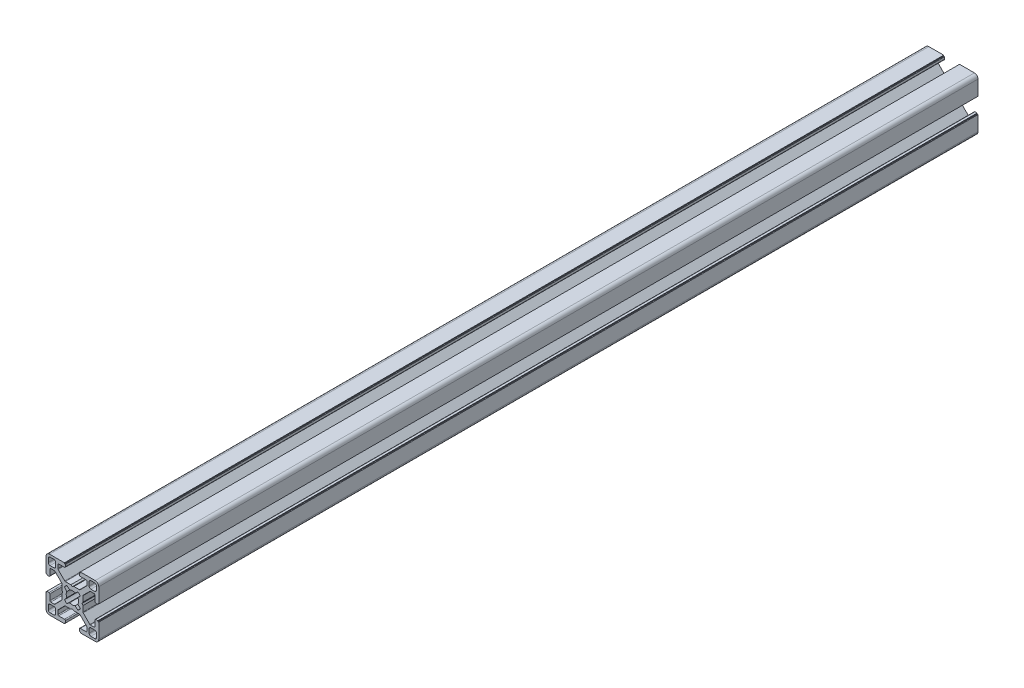
SolidWorks part; units mm, degrees
ref_plane "Front Plane" through (0, 0, 0) normal (0, 0, 1) x (1, 0, 0)
ref_plane "Top Plane" through (0, 0, 0) normal (0, 1, 0) x (1, 0, 0)
ref_plane "Right Plane" through (0, 0, 0) normal (1, 0, 0) x (0, 0, -1)
sketch "Sketch1" plane through (0, 0, 0) normal (0, 0, 1) x (1, 0, 0)
  line L0 (-15, 0) -> (15, 0) construction
  line L1 (0, -15) -> (0, 15) construction
  line L2 (-4.5, 15) -> (4.5, 15) construction
  line L3 (-4, -15) -> (4, -15) construction
  line L4 (-4.5, 15) -> (-4.5, 14.5)
  line L5 (-4.5, 14.5) -> (-4, 14.5)
  line L6 (-4, 14.5) -> (-4, 13.29)
  line L7 (-4.5, 12.79) -> (-7.7675, 12.79)
  line L8 (-8.2675, 12.29) -> (-8.2675, 10.2707)
  line L9 (-8.1211, 9.9171) -> (-4.3504, 6.1464)
  line L10 (-3.9968, 6) -> (0, 6)
  line L11 (0, 0) -> (-15, 15) construction
  line L12 (-4.5, 15) -> (-12.968, 15)
  line L14 (-12.705, 9.5135) -> (-10.5135, 9.5135)
  line L15 (-13.705, 10.5135) -> (-13.705, 12.705)
  line L16 (-12.705, 13.705) -> (-10.5135, 13.705)
  line L17 (-9.5135, 10.5135) -> (-9.5135, 12.705)
  line L18 (-13.705, 9.5135) -> (-9.5135, 13.705) construction
  line L19 (-13.705, 13.705) -> (-9.5135, 9.5135) construction
  line L20 (-3.1568, 4.5038) -> (-1.5303, 3.1477) construction
  line L21 (-4.5038, 3.1568) -> (-3.1477, 1.5303) construction
  line L22 (-6, 3.9968) -> (-6, 0)
  line L23 (-9.9171, 8.1211) -> (-6.1464, 4.3504)
  line L24 (-15, 4.5) -> (-15, 12.968)
  line L25 (-12.29, 8.2675) -> (-10.2707, 8.2675)
  line L26 (-12.79, 4.5) -> (-12.79, 7.7675)
  line L27 (-14.5, 4) -> (-13.29, 4)
  line L28 (-14.5, 4.5) -> (-14.5, 4)
  line L29 (-15, 4.5) -> (-14.5, 4.5)
  circle A0 centre (0, 0) radius 3.5
  arc A1 (-12.968, 15) -> (-15, 12.968) centre (-12.968, 12.968) ccw
  circle A2 centre (0, 0) radius 5.5 construction
  arc A3 (-10.5135, 9.5135) -> (-9.5135, 10.5135) centre (-10.5135, 10.5135) ccw
  arc A4 (-13.705, 12.705) -> (-12.705, 13.705) centre (-12.705, 12.705) cw
  arc A5 (-10.5135, 13.705) -> (-9.5135, 12.705) centre (-10.5135, 12.705) cw
  arc A6 (-12.705, 9.5135) -> (-13.705, 10.5135) centre (-12.705, 10.5135) cw
  arc A7 (-12.79, 4.5) -> (-13.29, 4) centre (-13.29, 4.5) cw
  arc A8 (-12.29, 8.2675) -> (-12.79, 7.7675) centre (-12.29, 7.7675) ccw
  arc A9 (-9.9171, 8.1211) -> (-10.2707, 8.2675) centre (-10.2707, 7.7675) ccw
  arc A10 (-6, 3.9968) -> (-6.1464, 4.3504) centre (-6.5, 3.9968) ccw
  arc A11 (-4.3504, 6.1464) -> (-3.9968, 6) centre (-3.9968, 6.5) ccw
  arc A12 (-4, 13.29) -> (-4.5, 12.79) centre (-4.5, 13.29) cw
  arc A13 (-7.7675, 12.79) -> (-8.2675, 12.29) centre (-7.7675, 12.29) ccw
  arc A14 (-8.2675, 10.2707) -> (-8.1211, 9.9171) centre (-7.7675, 10.2707) ccw
  point P4 (0, 0)
  point P8 (0, 0)
  point P13 (0, 15)
  point P15 (0, -15)
  point P16 (0, 6)
  point P23 (-11.6092, 11.6093)
  point P26 (0, 6)
  point P62 (-12.79, 4)
  point P65 (-12.79, 8.2675)
  point P68 (-10.0636, 8.2675)
  point P71 (-6, 4.2039)
  point P74 (-4.2039, 6)
  point P77 (-4, 12.79)
  point P80 (-8.2675, 12.79)
  point P83 (-8.2675, 10.0636)
  dimension "Center Hole Diameter" = 7
  dimension "D11" = 2.032
  dimension "D9" = 11
  dimension "D13" = 1
  dimension "D14" = 0.5
  dimension "Rail Height" = 30
  dimension "Rail Width" = 30
  dimension "T-Slot Width" = 8
  dimension "T-Slot Depth" = 9
  dimension "D1" = 9
  dimension "D2" = 45
  dimension "D3" = 8
  dimension "D4" = 2.21
  dimension "D5" = 16.535
  dimension "D7" = 2.54
  dimension "D6" = 1.295
  dimension "D8" = 1.246
  dimension "D10" = 10.36
  dimension "D12" = 1.905
sketch "Sketch2" plane through (0, 0, 0) normal (1, 0, 0) x (0, 0, -1)
  line L0 (-76.2, 0) -> (76.2, 0) construction
  line L2 (0, -15) -> (0, 15) construction
  line L3 (0, -15) -> (0, 15) construction
  line L4 (-76.2, -15) -> (-76.2, 15) construction
  line L5 (76.2, -15) -> (76.2, 15) construction
  point P0 (-38.7, 0)
  point P3 (0, 0)
  point P4 (38.7, 0)
  point P12 (-76.2, 0)
  point P14 (76.2, 0)
  dimension "Length" = 152.4
  dimension "D1" = 37.5
sketch "Sketch3" plane through (0, 0, 0) normal (0, 0, 1) x (1, 0, 0)
  line L0 (-4.5038, 3.1568) -> (-3.1477, 1.5303)
  line L1 (0, 3.5) -> (0, 5.5)
  line L2 (-5.5, 0) -> (-3.5, 0)
  line L7 (-6, 3.9968) -> (-6, 0) construction
  line L31 (-9.9171, 8.1211) -> (-6.1464, 4.3504) construction
  line L117 (-12.29, 8.2675) -> (-10.2707, 8.2675) construction
  line L118 (-12.79, 4.5) -> (-12.79, 7.7675) construction
  line L157 (-12.705, 9.5135) -> (-10.5135, 9.5135)
  line L158 (-9.5135, 10.5135) -> (-9.5135, 12.705)
  line L163 (-10.5135, 13.705) -> (-12.705, 13.705)
  line L164 (-13.705, 12.705) -> (-13.705, 10.5135)
  line L165 (-12.705, 9.5135) -> (-10.5135, 9.5135)
  line L166 (-9.5135, 10.5135) -> (-9.5135, 12.705)
  line L167 (-10.5135, 13.705) -> (-12.705, 13.705)
  line L168 (-13.705, 12.705) -> (-13.705, 10.5135)
  line L169 (-14.5, 4) -> (-13.29, 4) construction
  line L170 (-14.5, 4.5) -> (-14.5, 4) construction
  line L171 (-15, 4.5) -> (-14.5, 4.5) construction
  line L172 (-15, 4.5) -> (-15, 12.968) construction
  line L173 (-4.5, 15) -> (-12.968, 15) construction
  line L174 (-4.5, 15) -> (-4.5, 14.5) construction
  line L175 (-4.5, 14.5) -> (-4, 14.5) construction
  line L176 (-4, 14.5) -> (-4, 13.29) construction
  line L177 (-4.5, 12.79) -> (-7.7675, 12.79) construction
  line L178 (-8.2675, 12.29) -> (-8.2675, 10.2707) construction
  line L179 (-8.1211, 9.9171) -> (-4.3504, 6.1464) construction
  line L180 (-3.9968, 6) -> (0, 6) construction
  line L181 (-6, 3.9968) -> (-6, 0.866)
  line L182 (-9.9171, 8.1211) -> (-6.1464, 4.3504)
  line L183 (-12.29, 8.2675) -> (-10.2707, 8.2675)
  line L184 (-12.79, 4.5) -> (-12.79, 7.7675)
  line L185 (-14.5, 4) -> (-13.29, 4)
  line L186 (-14.5, 4.5) -> (-14.5, 4)
  line L187 (-15, 4.5) -> (-14.5, 4.5)
  line L188 (-15, 4.5) -> (-15, 12.968)
  line L189 (-4.5, 15) -> (-12.968, 15)
  line L190 (-4.5, 15) -> (-4.5, 14.5)
  line L191 (-4.5, 14.5) -> (-4, 14.5)
  line L192 (-4, 14.5) -> (-4, 13.29)
  line L193 (-4.5, 12.79) -> (-7.7675, 12.79)
  line L194 (-8.2675, 12.29) -> (-8.2675, 10.2707)
  line L195 (-8.1211, 9.9171) -> (-4.3504, 6.1464)
  line L196 (-3.9968, 6) -> (-0.866, 6)
  line L197 (-0.866, 6) -> (0, 5.5)
  line L198 (0, -15) -> (0, 15) construction
  line L199 (0, 0) -> (-15, 15) construction
  line L200 (0, 0) -> (-15, 15) construction
  line L201 (-3.1568, 4.5038) -> (-1.5303, 3.1477) construction
  line L202 (-3.1568, 4.5038) -> (-1.5303, 3.1477)
  line L203 (-6, 0.866) -> (-5.5, 0)
  line L204 (-15, 0) -> (15, 0) construction
  line L205 (-15, 0) -> (15, 0) construction
  line L206 (0, -15) -> (0, 15) construction
  arc A0 (-3.5, 0) -> (-3.1477, 1.5303) centre (0, 0) cw
  arc A10 (-6, 3.9968) -> (-6.1464, 4.3504) centre (-6.5, 3.9968) ccw construction
  circle A16 centre (0, 0) radius 3.5
  arc A18 (0, 3.5) -> (-1.5303, 3.1477) centre (0, 0) ccw
  arc A20 (-9.9171, 8.1211) -> (-10.2707, 8.2675) centre (-10.2707, 7.7675) ccw construction
  arc A22 (-12.29, 8.2675) -> (-12.79, 7.7675) centre (-12.29, 7.7675) ccw construction
  arc A28 (-13.29, 4) -> (-12.79, 4.5) centre (-13.29, 4.5) ccw construction
  arc A29 (-10.5135, 9.5135) -> (-9.5135, 10.5135) centre (-10.5135, 10.5135) ccw
  arc A30 (-9.5135, 12.705) -> (-10.5135, 13.705) centre (-10.5135, 12.705) ccw
  arc A31 (-12.705, 13.705) -> (-13.705, 12.705) centre (-12.705, 12.705) ccw
  arc A32 (-13.705, 10.5135) -> (-12.705, 9.5135) centre (-12.705, 10.5135) ccw
  arc A33 (-10.5135, 9.5135) -> (-9.5135, 10.5135) centre (-10.5135, 10.5135) ccw
  arc A34 (-9.5135, 12.705) -> (-10.5135, 13.705) centre (-10.5135, 12.705) ccw
  arc A35 (-12.705, 13.705) -> (-13.705, 12.705) centre (-12.705, 12.705) ccw
  arc A36 (-13.705, 10.5135) -> (-12.705, 9.5135) centre (-12.705, 10.5135) ccw
  arc A37 (-12.968, 15) -> (-15, 12.968) centre (-12.968, 12.968) ccw construction
  arc A38 (-4.5, 12.79) -> (-4, 13.29) centre (-4.5, 13.29) ccw construction
  arc A39 (-7.7675, 12.79) -> (-8.2675, 12.29) centre (-7.7675, 12.29) ccw construction
  arc A40 (-8.2675, 10.2707) -> (-8.1211, 9.9171) centre (-7.7675, 10.2707) ccw construction
  arc A41 (-4.3504, 6.1464) -> (-3.9968, 6) centre (-3.9968, 6.5) ccw construction
  arc A42 (-6, 3.9968) -> (-6.1464, 4.3504) centre (-6.5, 3.9968) ccw
  arc A43 (-9.9171, 8.1211) -> (-10.2707, 8.2675) centre (-10.2707, 7.7675) ccw
  arc A44 (-12.29, 8.2675) -> (-12.79, 7.7675) centre (-12.29, 7.7675) ccw
  arc A45 (-13.29, 4) -> (-12.79, 4.5) centre (-13.29, 4.5) ccw
  arc A46 (-12.968, 15) -> (-15, 12.968) centre (-12.968, 12.968) ccw
  arc A47 (-4.5, 12.79) -> (-4, 13.29) centre (-4.5, 13.29) ccw
  arc A48 (-7.7675, 12.79) -> (-8.2675, 12.29) centre (-7.7675, 12.29) ccw
  arc A49 (-8.2675, 10.2707) -> (-8.1211, 9.9171) centre (-7.7675, 10.2707) ccw
  arc A50 (-4.3504, 6.1464) -> (-3.9968, 6) centre (-3.9968, 6.5) ccw
  circle A51 centre (0, 0) radius 5.5 construction
  arc A52 (-3.1568, 4.5038) -> (-4.5038, 3.1568) centre (0, 0) ccw
  dimension "D3" = 60
  dimension "D4" = 60
  dimension "D1" = 0
  dimension "D2" = 0
extrude "Boss-Extrude1" add sketch "Sketch3" along normal mid plane 500
pattern_circular "CirPattern1" count 4 over 360 about axis through (0, 0, 0) along (0, 0, 1) of "Boss-Extrude1"
ref_plane "Contact Plane1" through (15, 0, 0) normal (1, 0, 0) x (0, 0, -1)
ref_plane "Contact Plane2" through (0, -15, 0) normal (0, 1, 0) x (1, 0, 0)
ref_plane "Contact Plane3" through (-15, 0, 0) normal (1, 0, 0) x (0, 0, -1)
ref_plane "Contact Plane4" through (0, 15, 0) normal (0, 1, 0) x (1, 0, 0)
equation "\"D1@Sketch2\" = \"Rail Height@Sketch1\" * 1.25"
equation "\"D1@Sketch1\"=\"T-Slot Width@Sketch1\"+1mm"
equation "\"D3@Sketch1\"=\"T-Slot Width@Sketch1\""
equation "\"D1@Boss-Extrude1\"=\"Length\""
equation "\"Length\" = 500"
